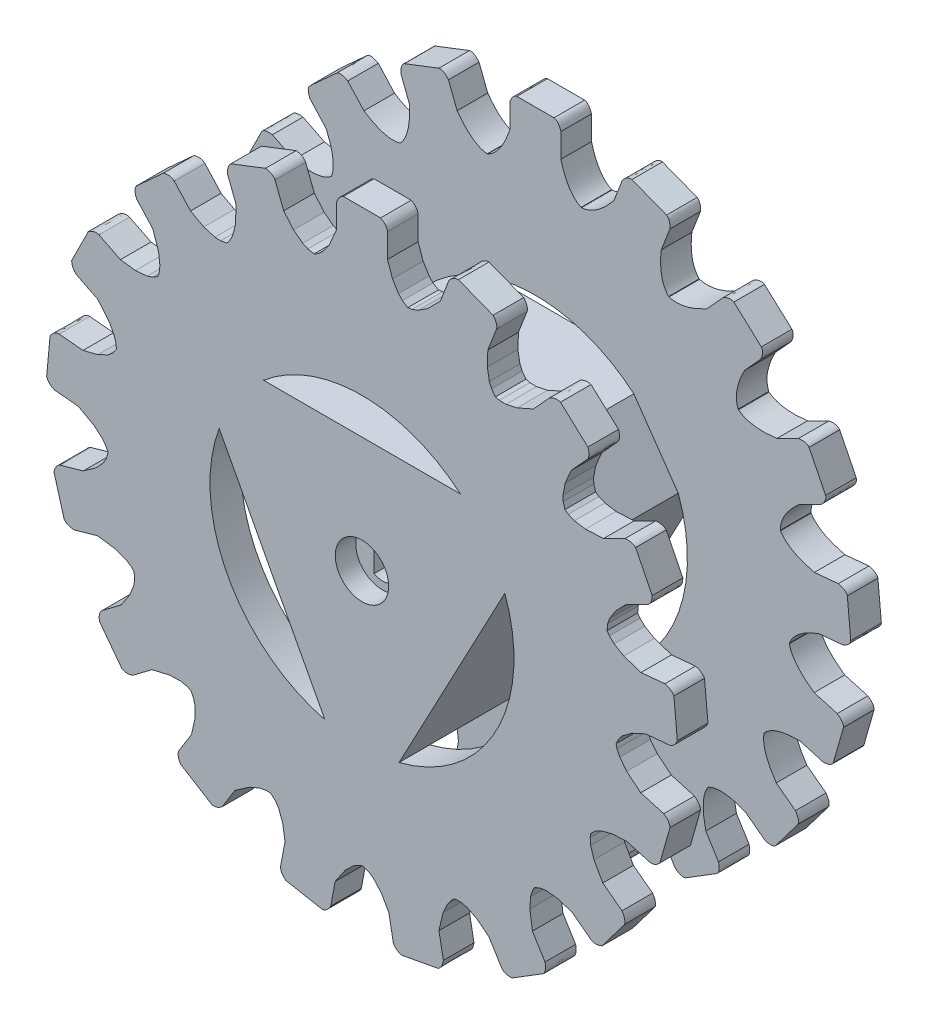
SolidWorks part; units mm, degrees
ref_plane "Front Plane" through (0, 0, 0) normal (0, 0, 1) x (1, 0, 0)
ref_plane "Top Plane" through (0, 0, 0) normal (0, 1, 0) x (1, 0, 0)
ref_plane "Right Plane" through (0, 0, 0) normal (1, 0, 0) x (0, 0, -1)
sketch "Sketch1" plane through (0, 0, 0) normal (0, 0, 1) x (1, 0, 0)
  line L0 (8.5238, 28.923) -> (7.6731, 26.7272)
  line L1 (-1.8223, 30.8747) -> (1.8223, 30.8747)
  line L2 (-2.5, 30.049) -> (-2.5, 27.6942)
  line L4 (2.5, 30.049) -> (2.5, 27.6942)
  line L5 (9.4539, 29.4481) -> (12.8525, 28.1315)
  line L6 (13.1861, 27.1167) -> (12.3355, 24.921)
  line L7 (18.3964, 23.8907) -> (16.8099, 22.1505)
  line L8 (19.4534, 24.0444) -> (22.1469, 21.589)
  line L9 (22.0914, 20.5222) -> (20.505, 18.782)
  line L10 (25.7844, 15.6319) -> (23.6765, 14.5823)
  line L11 (26.8256, 15.3933) -> (28.4502, 12.1307)
  line L12 (28.0131, 11.1561) -> (25.9052, 10.1065)
  line L13 (29.6901, 5.2619) -> (27.3454, 5.0446)
  line L14 (30.5748, 4.6633) -> (30.9111, 1.0342)
  line L15 (30.1515, 0.2832) -> (27.8067, 0.066)
  line L16 (29.5861, -5.8187) -> (27.3211, -5.1743)
  line L17 (30.1948, -6.6965) -> (29.1974, -10.202)
  line L18 (28.2177, -10.6279) -> (25.9528, -9.9834)
  line L19 (25.4862, -16.1135) -> (23.607, -14.6944)
  line L20 (25.7367, -17.1519) -> (23.5403, -20.0604)
  line L21 (22.473, -20.1036) -> (20.5939, -18.6845)
  line L22 (17.9443, -24.2321) -> (16.7047, -22.23)
  line L23 (17.8028, -25.2908) -> (14.704, -27.2095)
  line L24 (13.6932, -26.8643) -> (12.4536, -24.8622)
  line L25 (7.9789, -29.078) -> (7.5462, -26.7633)
  line L26 (7.4645, -30.0141) -> (3.8819, -30.6838)
  line L27 (3.0641, -29.9967) -> (2.6314, -27.682)
  line L28 (-3.0641, -29.9967) -> (-2.6314, -27.682)
  line L29 (-3.8819, -30.6838) -> (-7.4645, -30.0141)
  line L30 (-7.9789, -29.078) -> (-7.5462, -26.7633)
  line L31 (-13.6932, -26.8643) -> (-12.4536, -24.8622)
  line L32 (-14.704, -27.2095) -> (-17.8028, -25.2908)
  line L33 (-17.9443, -24.2321) -> (-16.7047, -22.23)
  line L34 (-22.473, -20.1036) -> (-20.5939, -18.6845)
  line L35 (-23.5403, -20.0604) -> (-25.7367, -17.1519)
  line L36 (-25.4862, -16.1135) -> (-23.607, -14.6944)
  line L37 (-28.2177, -10.6279) -> (-25.9528, -9.9834)
  line L38 (-29.1974, -10.202) -> (-30.1948, -6.6965)
  line L39 (-29.5861, -5.8187) -> (-27.3211, -5.1743)
  line L40 (-30.1515, 0.2832) -> (-27.8067, 0.066)
  line L41 (-30.9111, 1.0342) -> (-30.5748, 4.6633)
  line L42 (-29.6901, 5.2619) -> (-27.3454, 5.0446)
  line L43 (-28.0131, 11.1561) -> (-25.9052, 10.1065)
  line L44 (-28.4502, 12.1307) -> (-26.8256, 15.3933)
  line L45 (-25.7844, 15.6319) -> (-23.6765, 14.5823)
  line L46 (-22.0914, 20.5222) -> (-20.505, 18.782)
  line L47 (-22.1469, 21.589) -> (-19.4534, 24.0444)
  line L48 (-18.3964, 23.8907) -> (-16.8099, 22.1505)
  line L49 (-13.1861, 27.1167) -> (-12.3355, 24.921)
  line L50 (-12.8525, 28.1315) -> (-9.4539, 29.4481)
  line L51 (-8.5238, 28.923) -> (-7.6731, 26.7272)
  line L52 (3.6345, -14.4507) -> (14.0017, 5.0974)
  line L55 (-9.6443, 11.3587) -> (9.6443, 11.3587)
  line L59 (-14.0017, 5.0974) -> (-3.6345, -14.4507)
  arc A0 (-4.6728, 24.5594) -> (-4.7171, 24.5509) centre (0, 0) ccw
  arc A1 (-13.2291, 21.213) -> (-13.2674, 21.1891) centre (0, 0) ccw
  arc A2 (4.5146, 24.589) -> (4.4702, 24.5971) centre (0, 0) ccw
  arc A3 (13.0923, 21.2977) -> (13.0539, 21.3213) centre (0, 0) ccw
  arc A4 (19.9018, 15.13) -> (19.8745, 15.1659) centre (0, 0) ccw
  arc A5 (-19.9988, 15.0016) -> (-20.0259, 14.9655) centre (0, 0) ccw
  arc A6 (-24.0675, 6.7642) -> (-24.0797, 6.7207) centre (0, 0) ccw
  arc A7 (-24.8858, -2.3868) -> (-24.8815, -2.4317) centre (0, 0) ccw
  arc A8 (24.0235, 6.9189) -> (24.011, 6.9623) centre (0, 0) ccw
  arc A9 (24.9006, -2.2266) -> (24.9046, -2.1816) centre (0, 0) ccw
  arc A10 (22.4148, -11.0714) -> (22.4348, -11.0309) centre (0, 0) ccw
  arc A11 (16.9018, -18.4209) -> (16.935, -18.3904) centre (0, 0) ccw
  arc A12 (9.106, -23.2826) -> (9.148, -23.2662) centre (0, 0) ccw
  arc A13 (0.0804, -24.9999) -> (0.1256, -24.9997) centre (0, 0) ccw
  arc A14 (-8.956, -23.3407) -> (-8.9138, -23.3569) centre (0, 0) ccw
  arc A15 (-16.7829, -18.5293) -> (-16.7494, -18.5596) centre (0, 0) ccw
  arc A16 (-22.3431, -11.2154) -> (-22.3228, -11.2557) centre (0, 0) ccw
  arc A17 (3.6345, -14.4507) -> (14.0017, 5.0974) centre (0, 0) ccw
  arc A18 (-14.0017, 5.0974) -> (-3.6345, -14.4507) centre (0, 0) ccw
  arc A19 (9.6443, 11.3587) -> (-9.6443, 11.3587) centre (0, 0) ccw
  spline S0 degree 2 poles (-2.5, 27.6942) (-3.35, 25.1957) (-4.6728, 24.5594) knots 0 0 0 0.372776 0.372776 0.372776
  spline S1 degree 2 poles (2.5, 27.6942) (3.1474, 25.2334) (4.4702, 24.5971) knots 0 0 0 0.372776 0.372776 0.372776
  spline S2 degree 2 poles (-2.5, 30.049) (-2.2586, 30.7921) (-1.8223, 30.8747) knots 0 0 0 0.573783 0.573783 0.573783
  spline S3 degree 2 poles (2.5, 30.049) (2.2586, 30.7921) (1.8223, 30.8747) knots 0 0 0 0.573783 0.573783 0.573783
  spline S4 degree 2 poles (7.6731, 26.7272) (5.978, 24.7045) (4.5146, 24.589) knots 0 0 0 0.372776 0.372776 0.372776
  spline S5 degree 2 poles (8.5238, 28.923) (9.0173, 29.5287) (9.4539, 29.4481) knots 0 0 0 0.573783 0.573783 0.573783
  spline S6 degree 2 poles (13.1861, 27.1167) (13.2295, 27.8968) (12.8525, 28.1315) knots 0 0 0 0.573783 0.573783 0.573783
  spline S7 degree 2 poles (12.3355, 24.921) (12.0503, 22.3924) (13.0539, 21.3213) knots 0 0 0 0.372776 0.372776 0.372776
  spline S8 degree 2 poles (16.8099, 22.1505) (14.4986, 20.8767) (13.0923, 21.2977) knots 0 0 0 0.372776 0.372776 0.372776
  spline S9 degree 2 poles (18.3964, 23.8907) (19.0753, 24.2773) (19.4534, 24.0444) knots 0 0 0 0.573783 0.573783 0.573783
  spline S10 degree 2 poles (22.0914, 20.5222) (22.4136, 21.234) (22.1469, 21.589) knots 0 0 0 0.573783 0.573783 0.573783
  spline S11 degree 2 poles (20.505, 18.782) (19.3256, 16.5273) (19.8745, 15.1659) knots 0 0 0 0.372776 0.372776 0.372776
  spline S12 degree 2 poles (23.6765, 14.5823) (21.0611, 14.2295) (19.9018, 15.13) knots 0 0 0 0.372776 0.372776 0.372776
  spline S13 degree 2 poles (25.7844, 15.6319) (26.5572, 15.7471) (26.8256, 15.3933) knots 0 0 0 0.573783 0.573783 0.573783
  spline S14 degree 2 poles (28.0131, 11.1561) (28.5707, 11.7034) (28.4502, 12.1307) knots 0 0 0 0.573783 0.573783 0.573783
  spline S15 degree 2 poles (25.9052, 10.1065) (23.9909, 8.43) (24.011, 6.9623) knots 0 0 0 0.372776 0.372776 0.372776
  spline S16 degree 2 poles (27.3454, 5.0446) (24.7791, 5.6605) (24.0235, 6.9189) knots 0 0 0 0.372776 0.372776 0.372776
  spline S17 degree 2 poles (29.6901, 5.2619) (30.4523, 5.0901) (30.5748, 4.6633) knots 0 0 0 0.573783 0.573783 0.573783
  spline S18 degree 2 poles (30.1515, 0.2832) (30.8691, 0.5921) (30.9111, 1.0342) knots 0 0 0 0.573783 0.573783 0.573783
  spline S19 degree 2 poles (27.8067, 0.066) (25.4161, -0.8058) (24.9046, -2.1816) knots 0 0 0 0.372776 0.372776 0.372776
  spline S20 degree 2 poles (27.3211, -5.1743) (25.1506, -3.673) (24.9006, -2.2266) knots 0 0 0 0.372776 0.372776 0.372776
  spline S21 degree 2 poles (29.5861, -5.8187) (30.2347, -6.2542) (30.1948, -6.6965) knots 0 0 0 0.573783 0.573783 0.573783
  spline S22 degree 2 poles (28.2177, -10.6279) (28.9985, -10.5991) (29.1974, -10.202) knots 0 0 0 0.573783 0.573783 0.573783
  spline S23 degree 2 poles (25.9528, -9.9834) (23.4088, -9.9327) (22.4348, -11.0309) knots 0 0 0 0.372776 0.372776 0.372776
  spline S24 degree 2 poles (23.607, -14.6944) (22.1254, -12.5105) (22.4148, -11.0714) knots 0 0 0 0.372776 0.372776 0.372776
  spline S25 degree 2 poles (25.4862, -16.1135) (25.9337, -16.7539) (25.7367, -17.1519) knots 0 0 0 0.573783 0.573783 0.573783
  spline S26 degree 2 poles (22.473, -20.1036) (23.2115, -20.3588) (23.5403, -20.0604) knots 0 0 0 0.573783 0.573783 0.573783
  spline S27 degree 2 poles (20.5939, -18.6845) (18.2399, -17.7182) (16.935, -18.3904) knots 0 0 0 0.372776 0.372776 0.372776
  spline S28 degree 2 poles (16.7047, -22.23) (16.112, -19.6583) (16.9018, -18.4209) knots 0 0 0 0.372776 0.372776 0.372776
  spline S29 degree 2 poles (17.9443, -24.2321) (18.1303, -24.9909) (17.8028, -25.2908) knots 0 0 0 0.573783 0.573783 0.573783
  spline S30 degree 2 poles (13.6932, -26.8643) (14.2896, -27.369) (14.704, -27.2095) knots 0 0 0 0.573783 0.573783 0.573783
  spline S31 degree 2 poles (12.4536, -24.8622) (10.6077, -23.1108) (9.148, -23.2662) knots 0 0 0 0.372776 0.372776 0.372776
  spline S32 degree 2 poles (7.5462, -26.7633) (7.9226, -24.1511) (9.106, -23.2826) knots 0 0 0 0.372776 0.372776 0.372776
  spline S33 degree 2 poles (7.9789, -29.078) (7.8782, -29.8528) (7.4645, -30.0141) knots 0 0 0 0.573783 0.573783 0.573783
  spline S34 degree 2 poles (3.0641, -29.9967) (3.4378, -30.6828) (3.8819, -30.6838) knots 0 0 0 0.573783 0.573783 0.573783
  spline S35 degree 2 poles (2.6314, -27.682) (1.5428, -25.3821) (0.1256, -24.9997) knots 0 0 0 0.372776 0.372776 0.372776
  spline S36 degree 2 poles (-2.6314, -27.682) (-1.3367, -25.3823) (0.0804, -24.9999) knots 0 0 0 0.372776 0.372776 0.372776
  spline S37 degree 2 poles (-3.0641, -29.9967) (-3.4378, -30.6828) (-3.8819, -30.6838) knots 0 0 0 0.573783 0.573783 0.573783
  spline S38 degree 2 poles (-7.9789, -29.078) (-7.8782, -29.8528) (-7.4645, -30.0141) knots 0 0 0 0.573783 0.573783 0.573783
  spline S39 degree 2 poles (-7.5462, -26.7633) (-7.7305, -24.2254) (-8.9138, -23.3569) knots 0 0 0 0.372776 0.372776 0.372776
  spline S40 degree 2 poles (-12.4536, -24.8622) (-10.4156, -23.1854) (-8.956, -23.3407) knots 0 0 0 0.372776 0.372776 0.372776
  spline S41 degree 2 poles (-13.6932, -26.8643) (-14.2896, -27.369) (-14.704, -27.2095) knots 0 0 0 0.573783 0.573783 0.573783
  spline S42 degree 2 poles (-17.9443, -24.2321) (-18.1303, -24.9909) (-17.8028, -25.2908) knots 0 0 0 0.573783 0.573783 0.573783
  spline S43 degree 2 poles (-16.7047, -22.23) (-15.9597, -19.7969) (-16.7494, -18.5596) knots 0 0 0 0.372776 0.372776 0.372776
  spline S44 degree 2 poles (-20.5939, -18.6845) (-18.0878, -17.8572) (-16.7829, -18.5293) knots 0 0 0 0.372776 0.372776 0.372776
  spline S45 degree 2 poles (-22.473, -20.1036) (-23.2115, -20.3588) (-23.5403, -20.0604) knots 0 0 0 0.573783 0.573783 0.573783
  spline S46 degree 2 poles (-25.4862, -16.1135) (-25.9337, -16.7539) (-25.7367, -17.1519) knots 0 0 0 0.573783 0.573783 0.573783
  spline S47 degree 2 poles (-23.607, -14.6944) (-22.0334, -12.6948) (-22.3228, -11.2557) knots 0 0 0 0.372776 0.372776 0.372776
  spline S48 degree 2 poles (-25.9528, -9.9834) (-23.3171, -10.1172) (-22.3431, -11.2154) knots 0 0 0 0.372776 0.372776 0.372776
  spline S49 degree 2 poles (-28.2177, -10.6279) (-28.9985, -10.5991) (-29.1974, -10.202) knots 0 0 0 0.573783 0.573783 0.573783
  spline S50 degree 2 poles (-29.5861, -5.8187) (-30.2347, -6.2542) (-30.1948, -6.6965) knots 0 0 0 0.573783 0.573783 0.573783
  spline S51 degree 2 poles (-27.3211, -5.1743) (-25.1315, -3.8781) (-24.8815, -2.4317) knots 0 0 0 0.372776 0.372776 0.372776
  spline S52 degree 2 poles (-27.8067, 0.066) (-25.3973, -1.0109) (-24.8858, -2.3868) knots 0 0 0 0.372776 0.372776 0.372776
  spline S53 degree 2 poles (-30.1515, 0.2832) (-30.8691, 0.5921) (-30.9111, 1.0342) knots 0 0 0 0.573783 0.573783 0.573783
  spline S54 degree 2 poles (-29.6901, 5.2619) (-30.4523, 5.0901) (-30.5748, 4.6633) knots 0 0 0 0.573783 0.573783 0.573783
  spline S55 degree 2 poles (-27.3454, 5.0446) (-24.8353, 5.4623) (-24.0797, 6.7207) knots 0 0 0 0.372776 0.372776 0.372776
  spline S56 degree 2 poles (-25.9052, 10.1065) (-24.0475, 8.2319) (-24.0675, 6.7642) knots 0 0 0 0.372776 0.372776 0.372776
  spline S57 degree 2 poles (-28.0131, 11.1561) (-28.5707, 11.7034) (-28.4502, 12.1307) knots 0 0 0 0.573783 0.573783 0.573783
  spline S58 degree 2 poles (-25.7844, 15.6319) (-26.5572, 15.7471) (-26.8256, 15.3933) knots 0 0 0 0.573783 0.573783 0.573783
  spline S59 degree 2 poles (-23.6765, 14.5823) (-21.1851, 14.065) (-20.0259, 14.9655) knots 0 0 0 0.372776 0.372776 0.372776
  spline S60 degree 2 poles (-20.505, 18.782) (-19.4499, 16.363) (-19.9988, 15.0016) knots 0 0 0 0.372776 0.372776 0.372776
  spline S61 degree 2 poles (-22.0914, 20.5222) (-22.4136, 21.234) (-22.1469, 21.589) knots 0 0 0 0.573783 0.573783 0.573783
  spline S62 degree 2 poles (-18.3964, 23.8907) (-19.0753, 24.2773) (-19.4534, 24.0444) knots 0 0 0 0.573783 0.573783 0.573783
  spline S63 degree 2 poles (-16.8099, 22.1505) (-14.6736, 20.7681) (-13.2674, 21.1891) knots 0 0 0 0.372776 0.372776 0.372776
  spline S64 degree 2 poles (-12.3355, 24.921) (-12.2255, 22.2841) (-13.2291, 21.213) knots 0 0 0 0.372776 0.372776 0.372776
  spline S65 degree 2 poles (-13.1861, 27.1167) (-13.2295, 27.8968) (-12.8525, 28.1315) knots 0 0 0 0.573783 0.573783 0.573783
  spline S66 degree 2 poles (-8.5238, 28.923) (-9.0173, 29.5287) (-9.4539, 29.4481) knots 0 0 0 0.573783 0.573783 0.573783
  spline S67 degree 2 poles (-7.6731, 26.7272) (-6.1804, 24.6664) (-4.7171, 24.5509) knots 0 0 0 0.372776 0.372776 0.372776
  dimension "D1" = 50
  dimension "D2" = 17
extrude "Boss-Extrude2" add sketch "Sketch1" along normal blind 3
sketch "Sketch2" plane through (0, 0, 3) normal (0, 0, 1) x (1, 0, 0)
  line L0 (-14.0017, 5.0974) -> (-9.6443, 11.3587)
  line L1 (-9.6443, 11.3587) -> (9.6443, 11.3587)
  line L2 (9.6443, 11.3587) -> (14.0017, 5.0974)
  line L3 (14.0017, 5.0974) -> (3.6345, -14.4507)
  line L4 (3.6345, -14.4507) -> (-3.6345, -14.4507)
  line L5 (-3.6345, -14.4507) -> (-14.0017, 5.0974)
extrude "Boss-Extrude3" add sketch "Sketch2" along normal blind 14
sketch "Sketch3" plane through (0, 0, 17) normal (0, 0, 1) x (1, 0, 0)
  line L0 (-4.7171, 24.5509) -> (-4.3371, 24.7561)
  line L1 (-3.8537, 25.1795) -> (-3.2117, 26.0686)
  line L2 (-3.2117, 26.0686) -> (-2.5, 27.6942)
  line L3 (-2.5, 27.6942) -> (-2.5, 30.049)
  line L4 (-4.3371, 24.7561) -> (-3.8537, 25.1795)
  line L5 (-1.8223, 30.8747) -> (1.8223, 30.8747)
  line L6 (-0.1403, 24.7561) -> (-0.1403, 24.9932)
  line L7 (2.5, 30.049) -> (2.5, 27.6942)
  line L8 (2.5, 27.6942) -> (2.9903, 26.2914)
  line L9 (2.9903, 26.2914) -> (3.5787, 25.324)
  line L10 (3.9672, 24.9254) -> (4.5146, 24.589)
  line L11 (3.5787, 25.324) -> (3.9672, 24.9254)
  line L12 (1.8223, 30.8747) -> (-1.8223, 30.8747) construction
  line L13 (4.4702, 24.5971) -> (4.8987, 24.6512)
  line L14 (5.5024, 24.8713) -> (6.4222, 25.4685)
  line L15 (6.4222, 25.4685) -> (7.6731, 26.7272)
  line L16 (7.6731, 26.7272) -> (8.5238, 28.923)
  line L17 (9.4539, 29.4481) -> (12.8525, 28.1315)
  line L18 (13.1861, 27.1167) -> (12.3355, 24.921)
  line L19 (12.3355, 24.921) -> (12.2859, 23.4358)
  line L20 (12.2859, 23.4358) -> (12.4851, 22.3211)
  line L21 (12.4851, 22.3211) -> (12.7034, 21.8091)
  line L22 (12.7034, 21.8091) -> (13.0923, 21.2977)
  line L23 (4.8987, 24.6512) -> (5.5024, 24.8713)
  line L24 (13.0539, 21.3213) -> (13.4729, 21.2169)
  line L25 (14.1154, 21.2041) -> (15.1888, 21.4287)
  line L26 (15.1888, 21.4287) -> (16.8099, 22.1505)
  line L27 (16.8099, 22.1505) -> (18.3964, 23.8907)
  line L28 (19.4534, 24.0444) -> (22.1469, 21.589)
  line L29 (22.0914, 20.5222) -> (20.505, 18.782)
  line L30 (20.505, 18.782) -> (19.9223, 17.415)
  line L31 (19.9223, 17.415) -> (19.7054, 16.3036)
  line L32 (19.7054, 16.3036) -> (19.7239, 15.7474)
  line L33 (19.7239, 15.7474) -> (19.9018, 15.13)
  line L34 (13.4729, 21.2169) -> (14.1154, 21.2041)
  line L35 (19.8745, 15.1659) -> (20.2276, 14.9172)
  line L36 (20.8221, 14.6732) -> (21.9041, 14.4948)
  line L37 (21.9041, 14.4948) -> (23.6765, 14.5823)
  line L38 (23.6765, 14.5823) -> (25.7844, 15.6319)
  line L39 (26.8256, 15.3933) -> (28.4502, 12.1307)
  line L40 (28.0131, 11.1561) -> (25.9052, 10.1065)
  line L41 (25.9052, 10.1065) -> (24.868, 9.0423)
  line L42 (24.868, 9.0423) -> (24.2643, 8.0843)
  line L43 (24.2643, 8.0843) -> (24.0806, 7.5589)
  line L44 (24.0806, 7.5589) -> (24.0235, 6.9189)
  line L45 (20.2276, 14.9172) -> (20.8221, 14.6732)
  line L46 (24.011, 6.9623) -> (24.2504, 6.6028)
  line L47 (24.7166, 6.1605) -> (25.6611, 5.6034)
  line L48 (25.6611, 5.6034) -> (27.3454, 5.0446)
  line L49 (27.3454, 5.0446) -> (29.6901, 5.2619)
  line L50 (30.5748, 4.6633) -> (30.9111, 1.0342)
  line L51 (30.1515, 0.2832) -> (27.8067, 0.066)
  line L52 (27.8067, 0.066) -> (26.4551, -0.5517)
  line L53 (26.4551, -0.5517) -> (25.5461, -1.2269)
  line L54 (25.5461, -1.2269) -> (25.1851, -1.6505)
  line L55 (25.1851, -1.6505) -> (24.9006, -2.2266)
  line L56 (24.2504, 6.6028) -> (24.7166, 6.1605)
  line L57 (24.9046, -2.1816) -> (24.998, -2.6033)
  line L58 (25.2729, -3.1841) -> (25.9524, -4.0449)
  line L59 (25.9524, -4.0449) -> (27.3211, -5.1743)
  line L60 (27.3211, -5.1743) -> (29.5861, -5.8187)
  line L61 (30.1948, -6.6965) -> (29.1974, -10.202)
  line L62 (28.2177, -10.6279) -> (25.9528, -9.9834)
  line L63 (25.9528, -9.9834) -> (24.4694, -10.0711)
  line L64 (24.4694, -10.0711) -> (23.3779, -10.3724)
  line L65 (23.3779, -10.3724) -> (22.8882, -10.6369)
  line L66 (22.8882, -10.6369) -> (22.4148, -11.0714)
  line L67 (24.998, -2.6033) -> (25.2729, -3.1841)
  line L68 (22.4348, -11.0309) -> (22.3695, -11.4578)
  line L69 (22.4161, -12.0988) -> (22.7387, -13.1468)
  line L70 (22.7387, -13.1468) -> (23.607, -14.6944)
  line L71 (23.607, -14.6944) -> (25.4862, -16.1135)
  line L72 (25.7367, -17.1519) -> (23.5403, -20.0604)
  line L73 (22.473, -20.1036) -> (20.5939, -18.6845)
  line L74 (20.5939, -18.6845) -> (19.1789, -18.2304)
  line L75 (19.1789, -18.2304) -> (18.0523, -18.117)
  line L76 (18.0523, -18.117) -> (17.5001, -18.1868)
  line L77 (17.5001, -18.1868) -> (16.9018, -18.4209)
  line L78 (22.3695, -11.4578) -> (22.4161, -12.0988)
  line L79 (16.935, -18.3904) -> (16.7199, -18.7649)
  line L80 (16.5318, -19.3794) -> (16.454, -20.4732)
  line L81 (16.454, -20.4732) -> (16.7047, -22.23)
  line L82 (16.7047, -22.23) -> (17.9443, -24.2321)
  line L83 (17.8028, -25.2908) -> (14.704, -27.2095)
  line L84 (13.6932, -26.8643) -> (12.4536, -24.8622)
  line L85 (12.4536, -24.8622) -> (11.2982, -23.9276)
  line L86 (11.2982, -23.9276) -> (10.2886, -23.4148)
  line L87 (10.2886, -23.4148) -> (9.7485, -23.2804)
  line L88 (9.7485, -23.2804) -> (9.106, -23.2826)
  line L89 (16.7199, -18.7649) -> (16.5318, -19.3794)
  line L90 (9.148, -23.2662) -> (8.8122, -23.5377)
  line L91 (8.4148, -24.0427) -> (7.9472, -25.0346)
  line L92 (7.9472, -25.0346) -> (7.5462, -26.7633)
  line L93 (7.5462, -26.7633) -> (7.9789, -29.078)
  line L94 (7.4645, -30.0141) -> (3.8819, -30.6838)
  line L95 (3.0641, -29.9967) -> (2.6314, -27.682)
  line L96 (2.6314, -27.682) -> (1.8916, -26.3932)
  line L97 (1.8916, -26.3932) -> (1.1355, -25.5504)
  line L98 (1.1355, -25.5504) -> (0.6804, -25.2299)
  line L99 (0.6804, -25.2299) -> (0.0804, -24.9999)
  line L100 (8.8122, -23.5377) -> (8.4148, -24.0427)
  line L101 (0.1256, -24.9997) -> (-0.2857, -25.1316)
  line L102 (-0.8387, -25.4589) -> (-1.633, -26.2149)
  line L103 (-1.633, -26.2149) -> (-2.6314, -27.682)
  line L104 (-2.6314, -27.682) -> (-3.0641, -29.9967)
  line L105 (-3.8819, -30.6838) -> (-7.4645, -30.0141)
  line L106 (-7.9789, -29.078) -> (-7.5462, -26.7633)
  line L107 (-7.5462, -26.7633) -> (-7.7704, -25.2943)
  line L108 (-7.7704, -25.2943) -> (-8.1711, -24.2352)
  line L109 (-8.1711, -24.2352) -> (-8.4797, -23.772)
  line L110 (-8.4797, -23.772) -> (-8.956, -23.3407)
  line L111 (-0.2857, -25.1316) -> (-0.8387, -25.4589)
  line L112 (-8.9138, -23.3569) -> (-9.3449, -23.3313)
  line L113 (-9.9789, -23.4368) -> (-10.9927, -23.8548)
  line L114 (-10.9927, -23.8548) -> (-12.4536, -24.8622)
  line L115 (-12.4536, -24.8622) -> (-13.6932, -26.8643)
  line L116 (-14.704, -27.2095) -> (-17.8028, -25.2908)
  line L117 (-17.9443, -24.2321) -> (-16.7047, -22.23)
  line L118 (-16.7047, -22.23) -> (-16.3831, -20.7792)
  line L119 (-16.3831, -20.7792) -> (-16.3741, -19.6469)
  line L120 (-16.3741, -19.6469) -> (-16.4945, -19.1035)
  line L121 (-16.4945, -19.1035) -> (-16.7829, -18.5293)
  line L122 (-9.3449, -23.3313) -> (-9.9789, -23.4368)
  line L123 (-16.7494, -18.5596) -> (-17.1421, -18.38)
  line L124 (-17.7713, -18.2494) -> (-18.8677, -18.2729)
  line L125 (-18.8677, -18.2729) -> (-20.5939, -18.6845)
  line L126 (-20.5939, -18.6845) -> (-22.473, -20.1036)
  line L127 (-23.5403, -20.0604) -> (-25.7367, -17.1519)
  line L128 (-25.4862, -16.1135) -> (-23.607, -14.6944)
  line L129 (-23.607, -14.6944) -> (-22.783, -13.4578)
  line L130 (-22.783, -13.4578) -> (-22.3656, -12.4052)
  line L131 (-22.3656, -12.4052) -> (-22.2817, -11.855)
  line L132 (-22.2817, -11.855) -> (-22.3431, -11.2154)
  line L133 (-17.1421, -18.38) -> (-17.7713, -18.2494)
  line L134 (-22.3228, -11.2557) -> (-22.6242, -10.9464)
  line L135 (-23.1637, -10.5973) -> (-24.1945, -10.2232)
  line L136 (-24.1945, -10.2232) -> (-25.9528, -9.9834)
  line L137 (-25.9528, -9.9834) -> (-28.2177, -10.6279)
  line L138 (-29.1974, -10.202) -> (-30.1948, -6.6965)
  line L139 (-29.5861, -5.8187) -> (-27.3211, -5.1743)
  line L140 (-27.3211, -5.1743) -> (-26.1061, -4.3188)
  line L141 (-26.1061, -4.3188) -> (-25.3366, -3.4881)
  line L142 (-25.3366, -3.4881) -> (-25.0595, -3.0054)
  line L143 (-25.0595, -3.0054) -> (-24.8858, -2.3868)
  line L144 (-22.6242, -10.9464) -> (-23.1637, -10.5973)
  line L145 (-24.8815, -2.4317) -> (-25.0507, -2.0344)
  line L146 (-25.4277, -1.514) -> (-26.2538, -0.7927)
  line L147 (-26.2538, -0.7927) -> (-27.8067, 0.066)
  line L148 (-27.8067, 0.066) -> (-30.1515, 0.2832)
  line L149 (-30.9111, 1.0342) -> (-30.5748, 4.6633)
  line L150 (-29.6901, 5.2619) -> (-27.3454, 5.0446)
  line L151 (-27.3454, 5.0446) -> (-25.9033, 5.4034)
  line L152 (-25.9033, 5.4034) -> (-24.8857, 5.9001)
  line L153 (-24.8857, 5.9001) -> (-24.453, 6.2501)
  line L154 (-24.453, 6.2501) -> (-24.0675, 6.7642)
  line L155 (-25.0507, -2.0344) -> (-25.4277, -1.514)
  line L156 (-24.0797, 6.7207) -> (-24.094, 7.1523)
  line L157 (-24.2575, 7.7738) -> (-24.7673, 8.7448)
  line L158 (-24.7673, 8.7448) -> (-25.9052, 10.1065)
  line L159 (-25.9052, 10.1065) -> (-28.0131, 11.1561)
  line L160 (-28.4502, 12.1307) -> (-26.8256, 15.3933)
  line L161 (-25.7844, 15.6319) -> (-23.6765, 14.5823)
  line L162 (-23.6765, 14.5823) -> (-22.2022, 14.3959)
  line L163 (-22.2022, 14.3959) -> (-21.0739, 14.4914)
  line L164 (-21.0739, 14.4914) -> (-20.5439, 14.6615)
  line L165 (-20.5439, 14.6615) -> (-19.9988, 15.0016)
  line L166 (-24.094, 7.1523) -> (-24.2575, 7.7738)
  line L167 (-20.0259, 14.9655) -> (-19.8833, 15.3731)
  line L168 (-19.8113, 16.0117) -> (-19.9358, 17.1012)
  line L169 (-19.9358, 17.1012) -> (-20.505, 18.782)
  line L170 (-20.505, 18.782) -> (-22.0914, 20.5222)
  line L171 (-22.1469, 21.589) -> (-19.4534, 24.0444)
  line L172 (-18.3964, 23.8907) -> (-16.8099, 22.1505)
  line L173 (-16.8099, 22.1505) -> (-15.5025, 21.4441)
  line L174 (-15.5025, 21.4441) -> (-14.4159, 21.1256)
  line L175 (-14.4159, 21.1256) -> (-13.8603, 21.0928)
  line L176 (-13.8603, 21.0928) -> (-13.2291, 21.213)
  line L177 (-19.8833, 15.3731) -> (-19.8113, 16.0117)
  line L178 (-13.2674, 21.1891) -> (-12.9872, 21.5177)
  line L179 (-12.6894, 22.0871) -> (-12.4119, 23.1481)
  line L180 (-12.4119, 23.1481) -> (-12.3355, 24.921)
  line L181 (-12.3355, 24.921) -> (-13.1861, 27.1167)
  line L182 (-12.8525, 28.1315) -> (-9.4539, 29.4481)
  line L183 (-8.5238, 28.923) -> (-7.6731, 26.7272)
  line L184 (-7.6731, 26.7272) -> (-6.7092, 25.5962)
  line L185 (-6.7092, 25.5962) -> (-5.811, 24.9067)
  line L186 (-5.811, 24.9067) -> (-5.3048, 24.6753)
  line L187 (-5.3048, 24.6753) -> (-4.6728, 24.5594)
  line L188 (-12.9872, 21.5177) -> (-12.6894, 22.0871)
  line L189 (-14.0017, 5.0974) -> (-3.6345, -14.4507)
  line L190 (-14.0017, 5.0974) -> (-3.6345, -14.4507) construction
  line L191 (-9.6443, 11.3587) -> (9.6443, 11.3587)
  line L192 (3.6345, -14.4507) -> (14.0017, 5.0974)
  line L193 (14.0017, 5.0974) -> (3.6345, -14.4507)
  line L194 (9.6443, 11.3587) -> (-9.6443, 11.3587)
  line L195 (-3.6345, -14.4507) -> (-14.0017, 5.0974)
  arc A1 (3.6345, -14.4507) -> (14.0017, 5.0974) centre (0, 0) ccw
  arc A2 (-14.0017, 5.0974) -> (-3.6345, -14.4507) centre (0, 0) ccw
  arc A3 (9.6443, 11.3587) -> (-9.6443, 11.3587) centre (0, 0) ccw
  parabola Q0 (-2.5, 27.6942) -> (-4.6728, 24.5594) focus (-5.3497, 25.4535) apex (-5.0846, 24.4093) construction
  parabola Q1 (-2.5, 27.6942) -> (-4.6728, 24.5594) focus (-5.3497, 25.4535) apex (-5.0846, 24.4093) construction
  parabola Q2 (-1.8223, 30.8747) -> (-2.5, 30.049) focus (-1.7974, 30.5894) apex (-1.8776, 30.8613) construction
  parabola Q3 (4.4702, 24.5971) -> (2.5, 27.6942) focus (5.0417, 25.5458) apex (4.6606, 24.5162) construction
  parabola Q4 (4.4702, 24.5971) -> (2.5, 27.6942) focus (5.0417, 25.5458) apex (4.6606, 24.5162) construction
  parabola Q5 (-2.5, 27.6942) -> (-4.6728, 24.5594) focus (-5.3497, 25.4535) apex (-5.0846, 24.4093) construction
  parabola Q6 (4.4702, 24.5971) -> (2.5, 27.6942) focus (5.0417, 25.5458) apex (4.6606, 24.5162) construction
  parabola Q7 (-1.8223, 30.8747) -> (-2.5, 30.049) focus (-1.7974, 30.5894) apex (-1.8776, 30.8613) construction
  spline S0 degree 2 poles (-2.5, 30.049) (-2.2893, 30.6779) (-1.8223, 30.8747) knots 0 0 0 0.746925 0.746925 0.746925
  spline S1 degree 2 poles (1.8223, 30.8747) (2.4442, 30.5419) (2.5, 30.049) knots 0 0 0 0.688261 0.688261 0.688261
  spline S2 degree 2 poles (8.5238, 28.923) (8.9474, 29.4333) (9.4539, 29.4481) knots 0 0 0 0.746925 0.746925 0.746925
  spline S3 degree 2 poles (12.8525, 28.1315) (13.3122, 27.5965) (13.1861, 27.1167) knots 0 0 0 0.688261 0.688261 0.688261
  spline S4 degree 2 poles (18.3964, 23.8907) (18.9757, 24.2136) (19.4534, 24.0444) knots 0 0 0 0.746925 0.746925 0.746925
  spline S5 degree 2 poles (22.1469, 21.589) (22.3822, 20.9241) (22.0914, 20.5222) knots 0 0 0 0.688261 0.688261 0.688261
  spline S6 degree 2 poles (25.7844, 15.6319) (26.4413, 15.7236) (26.8256, 15.3933) knots 0 0 0 0.746925 0.746925 0.746925
  spline S7 degree 2 poles (28.4502, 12.1307) (28.4295, 11.4257) (28.0131, 11.1561) knots 0 0 0 0.688261 0.688261 0.688261
  spline S8 degree 2 poles (29.6901, 5.2619) (30.3358, 5.1102) (30.5748, 4.6633) knots 0 0 0 0.746925 0.746925 0.746925
  spline S9 degree 2 poles (30.9111, 1.0342) (30.6371, 0.3843) (30.1515, 0.2832) knots 0 0 0 0.688261 0.688261 0.688261
  spline S10 degree 2 poles (29.5861, -5.8187) (30.1333, -6.1935) (30.1948, -6.6965) knots 0 0 0 0.746925 0.746925 0.746925
  spline S11 degree 2 poles (29.1974, -10.202) (28.7071, -10.7091) (28.2177, -10.6279) knots 0 0 0 0.688261 0.688261 0.688261
  spline S12 degree 2 poles (25.4862, -16.1135) (25.8611, -16.6606) (25.7367, -17.1519) knots 0 0 0 0.746925 0.746925 0.746925
  spline S13 degree 2 poles (23.5403, -20.0604) (22.9, -20.3561) (22.473, -20.1036) knots 0 0 0 0.688261 0.688261 0.688261
  spline S14 degree 2 poles (17.9443, -24.2321) (18.0963, -24.8777) (17.8028, -25.2908) knots 0 0 0 0.746925 0.746925 0.746925
  spline S15 degree 2 poles (14.704, -27.2095) (14.0001, -27.2539) (13.6932, -26.8643) knots 0 0 0 0.688261 0.688261 0.688261
  spline S16 degree 2 poles (7.9789, -29.078) (7.8874, -29.7349) (7.4645, -30.0141) knots 0 0 0 0.746925 0.746925 0.746925
  spline S17 degree 2 poles (3.8819, -30.6838) (3.2095, -30.471) (3.0641, -29.9967) knots 0 0 0 0.688261 0.688261 0.688261
  spline S18 degree 2 poles (-3.0641, -29.9967) (-3.3867, -30.5762) (-3.8819, -30.6838) knots 0 0 0 0.746925 0.746925 0.746925
  spline S19 degree 2 poles (-7.4645, -30.0141) (-8.0146, -29.5727) (-7.9789, -29.078) knots 0 0 0 0.688261 0.688261 0.688261
  spline S20 degree 2 poles (-13.6932, -26.8643) (-14.2034, -27.2881) (-14.704, -27.2095) knots 0 0 0 0.746925 0.746925 0.746925
  spline S21 degree 2 poles (-17.8028, -25.2908) (-18.1563, -24.6805) (-17.9443, -24.2321) knots 0 0 0 0.688261 0.688261 0.688261
  spline S22 degree 2 poles (-22.473, -20.1036) (-23.1019, -20.3145) (-23.5403, -20.0604) knots 0 0 0 0.746925 0.746925 0.746925
  spline S23 degree 2 poles (-25.7367, -17.1519) (-25.8459, -16.4551) (-25.4862, -16.1135) knots 0 0 0 0.688261 0.688261 0.688261
  spline S24 degree 2 poles (-28.2177, -10.6279) (-28.8803, -10.5973) (-29.1974, -10.202) knots 0 0 0 0.746925 0.746925 0.746925
  spline S25 degree 2 poles (-30.1948, -6.6965) (-30.0449, -6.0073) (-29.5861, -5.8187) knots 0 0 0 0.688261 0.688261 0.688261
  spline S26 degree 2 poles (-30.1515, 0.2832) (-30.7583, 0.551) (-30.9111, 1.0342) knots 0 0 0 0.746925 0.746925 0.746925
  spline S27 degree 2 poles (-30.5748, 4.6633) (-30.1861, 5.2518) (-29.6901, 5.2619) knots 0 0 0 0.688261 0.688261 0.688261
  spline S28 degree 2 poles (-28.0131, 11.1561) (-28.4822, 11.625) (-28.4502, 12.1307) knots 0 0 0 0.746925 0.746925 0.746925
  spline S29 degree 2 poles (-26.8256, 15.3933) (-26.2505, 15.8016) (-25.7844, 15.6319) knots 0 0 0 0.688261 0.688261 0.688261
  spline S30 degree 2 poles (-22.0914, 20.5222) (-22.3594, 21.1289) (-22.1469, 21.589) knots 0 0 0 0.746925 0.746925 0.746925
  spline S31 degree 2 poles (-19.4534, 24.0444) (-18.7697, 24.2174) (-18.3964, 23.8907) knots 0 0 0 0.688261 0.688261 0.688261
  spline S32 degree 2 poles (-13.1861, 27.1167) (-13.2169, 27.7793) (-12.8525, 28.1315) knots 0 0 0 0.746925 0.746925 0.746925
  spline S33 degree 2 poles (-9.4539, 29.4481) (-8.7539, 29.3624) (-8.5238, 28.923) knots 0 0 0 0.688261 0.688261 0.688261
  dimension "D1" = 17
extrude "Boss-Extrude7" add sketch "Sketch3" along normal blind 3
sketch "Sketch6" plane through (0, 0, 20) normal (0, 0, 1) x (1, 0, 0)
  line L2 (0.8865, -1.6238) -> (0.8865, 1.6481)
  line L3 (0.8865, 1.6481) -> (0.8404, 1.6481)
  line L4 (-0.8295, -1.6536) -> (-0.8295, 1.6536)
  circle A0 centre (0, 0) radius 1.85
  point P8 (-0.8295, -1.6536)
  dimension "D1" = 3.7
extrude "Cut-Extrude1" cut sketch "Sketch6" against normal blind 10 contours L2 A0 L4
sketch "Sketch7" plane through (0, 0, 20) normal (0, 0, 1) x (1, 0, 0)
  circle A0 centre (0, 0) radius 2.616
extrude "Cut-Extrude3" cut sketch "Sketch7" against normal blind 2
sketch "Sketch8" plane through (0, 0, 0) normal (0, 0, -1) x (-1, 0, 0)
  line L1 (0, -5.9927) -> (5.1898, -2.9963)
  line L2 (5.1898, -2.9963) -> (5.1898, 2.9963)
  line L3 (5.1898, 2.9963) -> (0, 5.9927)
  line L4 (0, 5.9927) -> (-5.1898, 2.9963)
  line L5 (-5.1898, 2.9963) -> (-5.1898, -2.9963)
  line L6 (-5.1898, -2.9963) -> (0, -5.9927)
  circle A0 centre (0, 0) radius 5.1898 construction
extrude "Boss-Extrude10" add sketch "Sketch8" along normal blind 5
